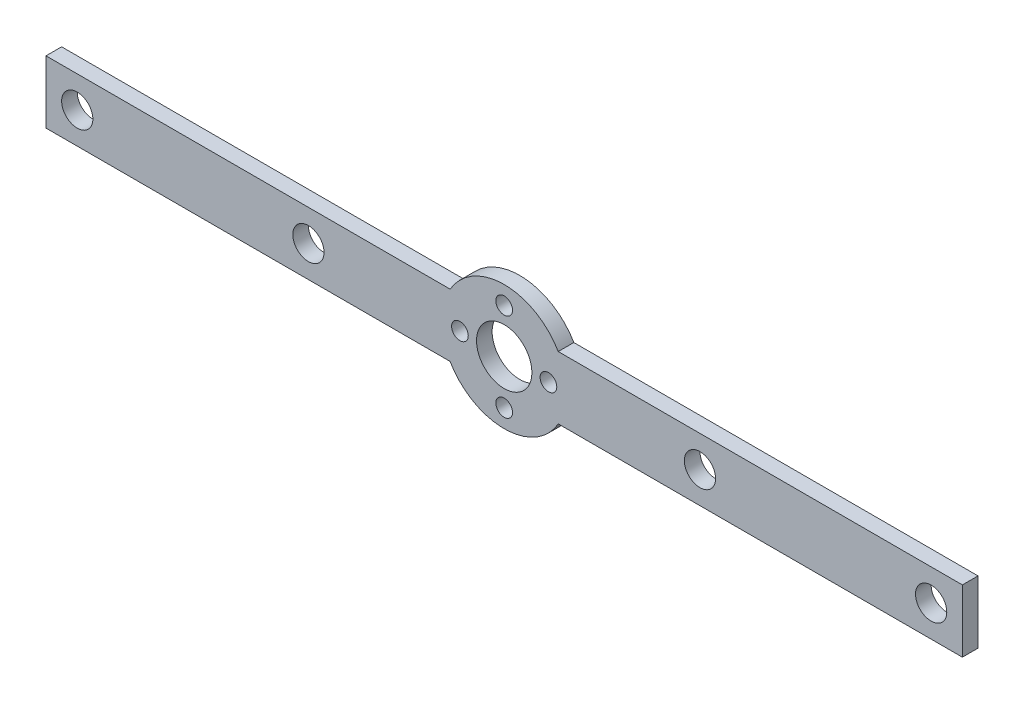
SolidWorks part; units mm, degrees
material "Thornel Mat VMA"
ref_plane "前视基准面" through (0, 0, 0) normal (0, 0, 1) x (1, 0, 0)
ref_plane "上视基准面" through (0, 0, 0) normal (0, 1, 0) x (1, 0, 0)
ref_plane "右视基准面" through (0, 0, 0) normal (1, 0, 0) x (0, 0, -1)
other "Configuration Table"
sketch "草图2" plane through (0, 0, 0) normal (0, 0, 1) x (1, 0, 0)
  line L0 (5.1884, -15.9867) -> (44, -15.9867)
  line L1 (-44, -22) -> (-5.1962, -22)
  line L2 (-44, -22) -> (-44, -15.9867)
  line L3 (-44, -15.9867) -> (-5.1884, -15.9867)
  line L4 (44, -22) -> (44, -15.9867)
  line L5 (5.1962, -22) -> (44, -22)
  circle A0 centre (41, -19) radius 1.5
  circle A1 centre (-41, -19) radius 1.5
  arc A2 (-5.1962, -22) -> (5.1962, -22) centre (0, -19) ccw
  circle A3 centre (4.25, -19) radius 0.8
  circle A4 centre (-4.25, -19) radius 0.8
  arc A5 (5.1884, -15.9867) -> (-5.1884, -15.9867) centre (0, -19) ccw
  circle A6 centre (0, -14.75) radius 0.8
  circle A7 centre (0, -23.25) radius 0.8
  circle A8 centre (0, -19) radius 2.66
  circle A9 centre (-18.8, -19) radius 1.5
  circle A10 centre (18.8, -19) radius 1.5
  point P22 (0, -19)
  dimension "D1" = 44
  dimension "D2" = 4.25
  dimension "D3" = 4.25
  dimension "D4" = 4.25
  dimension "D5" = 4.25
extrude "凸台-拉伸1" add sketch "草图2" along normal blind 1.5
